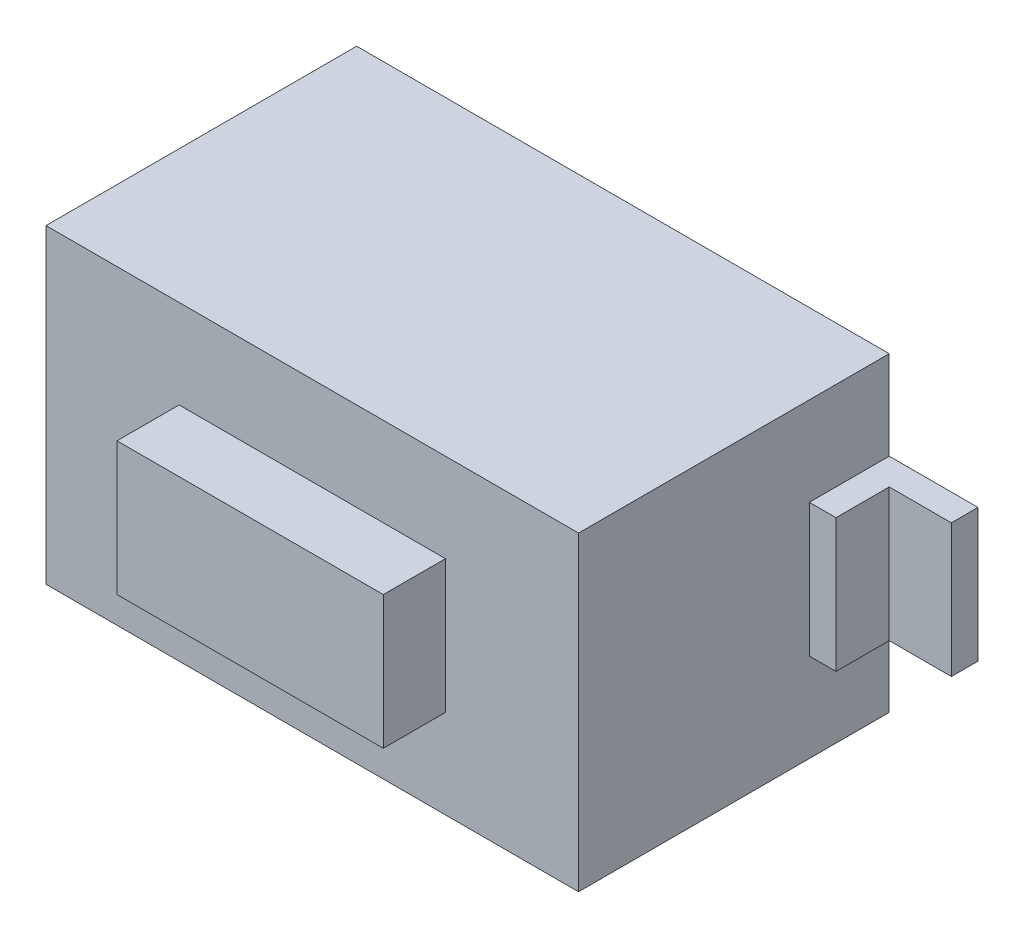
SolidWorks part; units mm, degrees
other "Camera1"
ref_plane "Front Plane" through (0, 0, 0) normal (0, 0, 1) x (1, 0, 0)
ref_plane "Top Plane" through (0, 0, 0) normal (0, 1, 0) x (1, 0, 0)
ref_plane "Right Plane" through (0, 0, 0) normal (1, 0, 0) x (0, 0, -1)
sketch "Sketch1" plane through (0, 0, 0) normal (0, 0, 1) x (1, 0, 0)
  line L1 (-3, -1.75) -> (3, -1.75)
  line L2 (-3, -1.75) -> (-3, 1.75)
  line L3 (-3, 1.75) -> (3, 1.75)
  line L4 (3, -1.75) -> (3, 1.75)
  line L5 (-3, -1.75) -> (3, 1.75) construction
  line L6 (-3, 1.75) -> (3, -1.75) construction
  point P0 (0, 0)
  dimension "D1" = 6
  dimension "D2" = 3.5
extrude "Boss-Extrude1" add sketch "Sketch1" along normal blind 3.5
sketch "Sketch2" plane through (0, 0, 3.5) normal (0, 0, 1) x (1, 0, 0)
  line L1 (1.5, 0.75) -> (-1.5, 0.75)
  line L2 (1.5, 0.75) -> (1.5, -0.75)
  line L3 (1.5, -0.75) -> (-1.5, -0.75)
  line L4 (-1.5, 0.75) -> (-1.5, -0.75)
  line L5 (1.5, 0.75) -> (-1.5, -0.75) construction
  line L6 (1.5, -0.75) -> (-1.5, 0.75) construction
  point P0 (0, 0)
  dimension "D1" = 3
  dimension "D2" = 1.5
extrude "Boss-Extrude2" add sketch "Sketch2" along normal blind 0.7
sketch "Sketch3" plane through (-3, 0, 0) normal (-1, 0, 0) x (0, 0, 1)
  line L1 (0, 0.75) -> (0.3, 0.75)
  line L2 (0, 0.75) -> (0, -0.75)
  line L3 (0, -0.75) -> (0.3, -0.75)
  line L4 (0.3, 0.75) -> (0.3, -0.75)
  line L5 (0, 0.75) -> (0.3, -0.75) construction
  line L6 (0, -0.75) -> (0.3, 0.75) construction
  point P0 (0, 0)
  dimension "D1" = 1.5
  dimension "D2" = 0.3
extrude "Boss-Extrude3" add sketch "Sketch3" along normal blind 1
sketch "Sketch4" plane through (0, 0, 0.3) normal (0, 0, 1) x (1, 0, 0)
  line L0 (-3, -0.75) -> (-3, 0.75) construction
  line L1 (-3, -0.75) -> (-3.3, -0.75)
  line L2 (-3, -0.75) -> (-3, 0.75)
  line L3 (-3, 0.75) -> (-3.3, 0.75)
  line L4 (-3.3, -0.75) -> (-3.3, 0.75)
  line L5 (-3, -0.75) -> (-3.3, 0.75) construction
  line L6 (-3, 0.75) -> (-3.3, -0.75) construction
  point P0 (-3.15, 0)
  point P5 (-3, 0)
  point P8 (-3, 0)
  dimension "D1" = 0.3
  dimension "D2" = 1.5
extrude "Boss-Extrude4" add sketch "Sketch4" along normal blind 0.6
mirror "Mirror1" about plane through (0, 0, 0) normal (1, 0, 0) of "Boss-Extrude4", "Boss-Extrude3"
